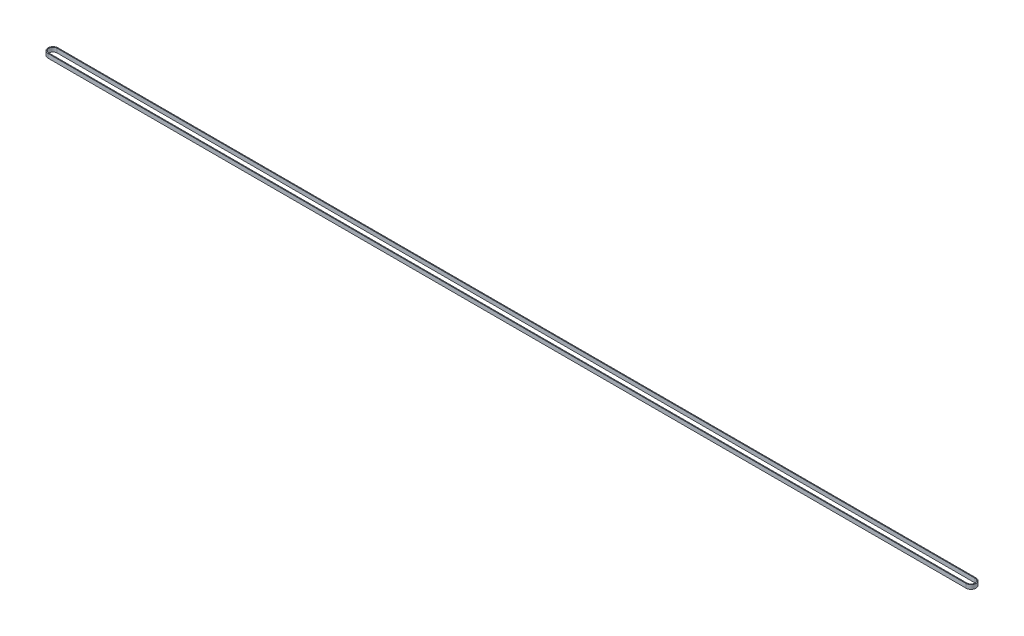
SolidWorks part; units mm, degrees
ref_plane "Front Plane" through (0, 0, 0) normal (0, 0, 1) x (1, 0, 0)
ref_plane "Top Plane" through (0, 0, 0) normal (0, 1, 0) x (1, 0, 0)
ref_plane "Right Plane" through (0, 0, 0) normal (1, 0, 0) x (0, 0, -1)
sketch "Sketch1" plane through (0, 0, 0) normal (0, 1, 0) x (1, 0, 0)
  line L0 (-557.95, 0) -> (557.95, 0) construction
  line L1 (-557.95, 5) -> (557.95, 5)
  line L2 (-557.95, -5) -> (557.95, -5)
  line L3 (-557.95, 6) -> (557.95, 6)
  line L4 (-557.95, -6) -> (557.95, -6)
  arc A0 (-557.95, 5) -> (-557.95, -5) centre (-557.95, 0) ccw
  arc A1 (557.95, -5) -> (557.95, 5) centre (557.95, 0) ccw
  arc A2 (557.95, -6) -> (557.95, 6) centre (557.95, 0) ccw
  arc A3 (-557.95, 6) -> (-557.95, -6) centre (-557.95, 0) ccw
  point P2 (0, 0)
  point P14 (0, 0)
  dimension "D2" = 6
  dimension "D1" = 1
  dimension "D3" = 1115.9
extrude "Boss-Extrude1" add sketch "Sketch1" along normal mid plane 5 contours L2 A1 L1 A0
